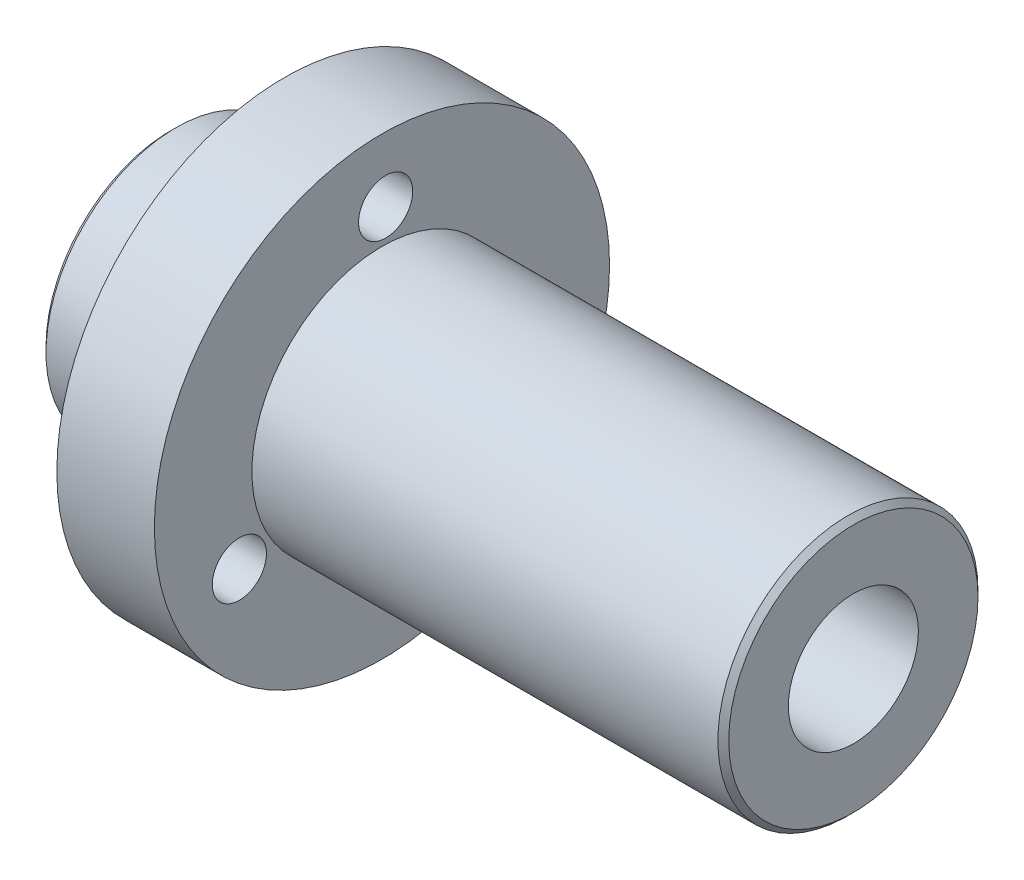
SolidWorks part; units mm, degrees
ref_plane "Plan de face" through (0, 0, 0) normal (0, 0, 1) x (1, 0, 0)
ref_plane "Plan de dessus" through (0, 0, 0) normal (0, 1, 0) x (1, 0, 0)
ref_plane "Plan de droite" through (0, 0, 0) normal (1, 0, 0) x (0, 0, -1)
sketch "Esquisse1" plane through (0, 0, 0) normal (0, 0, 1) x (1, 0, 0)
  line L0 (21, 42) -> (21, 0)
  line L1 (21, 0) -> (39, 0)
  line L2 (39, 0) -> (39, 42)
  line L3 (39, 42) -> (21, 42)
  line L4 (21, 0) -> (39, 0) construction
revolve "Révolution1" add sketch "Esquisse1" angle 360 about L4
sketch "Esquisse2" plane through (21, 0, 0) normal (-1, 0, 0) x (0, 0, 1)
  circle A0 centre (0, 0) radius 24
extrude "Extrusion1" add sketch "Esquisse2" along normal blind 21
sketch "Esquisse3" plane through (39, 0, 0) normal (1, 0, 0) x (0, 0, -1)
  circle A0 centre (0, 0) radius 24
extrude "Extrusion2" add sketch "Esquisse3" along normal blind 87
hole_wizard "Diamètre du perçage M10.0 (10)1" positions "Esquisse5" profile "Esquisse4" hole size "M10.0" standard "Ansi Métrique"
sketch "Esquisse5" plane through (39, 0, 0) normal (1, 0, 0) x (0, 0, -1)
  point P0 (25.6331, -15.5866)
sketch "Esquisse4" plane through (39, -15.5866, -25.6331) normal (0, 1, 0) x (0, 0, -1)
  line L0 (0, 0) -> (0, 18)
  line L1 (0, 18) -> (5, 18)
  line L2 (5, 18) -> (5, 0)
  line L5 (5, 0) -> (0, 0)
  line L11 (0, -6.35) -> (0, 107.95) construction
  dimension "Diamètre du perçage jusqu'au prochain" = 10
  dimension "Profondeur du perçage jusqu'au prochain" = 18
hole_wizard "Diamètre du perçage M10.0 (10)2" positions "Esquisse7" profile "Esquisse6" hole size "M10.0" standard "Ansi Métrique"
sketch "Esquisse7" plane through (39, 0, 0) normal (1, 0, 0) x (0, 0, -1)
  point P0 (0.6818, 29.9923)
sketch "Esquisse6" plane through (39, 29.9923, -0.6818) normal (0, 1, 0) x (0, 0, -1)
  line L0 (0, 0) -> (0, 18)
  line L1 (0, 18) -> (5, 18)
  line L2 (5, 18) -> (5, 0)
  line L5 (5, 0) -> (0, 0)
  line L11 (0, -6.35) -> (0, 107.95) construction
  dimension "Diamètre du perçage jusqu'au prochain" = 10
  dimension "Profondeur du perçage jusqu'au prochain" = 18
hole_wizard "Diamètre du perçage M10.0 (10)3" positions "Esquisse9" profile "Esquisse8" hole size "M10.0" standard "Ansi Métrique"
sketch "Esquisse9" plane through (39, 0, 0) normal (1, 0, 0) x (0, 0, -1)
  point P0 (-26.315, -14.4056)
sketch "Esquisse8" plane through (39, -14.4056, 26.315) normal (0, 1, 0) x (0, 0, -1)
  line L0 (0, 0) -> (0, 18)
  line L1 (0, 18) -> (5, 18)
  line L2 (5, 18) -> (5, 0)
  line L5 (5, 0) -> (0, 0)
  line L11 (0, -6.35) -> (0, 107.95) construction
  dimension "Diamètre du perçage jusqu'au prochain" = 10
  dimension "Profondeur du perçage jusqu'au prochain" = 18
hole_wizard "Perçage1" positions "Esquisse11" profile "Esquisse10" legacy end condition up to next
sketch "Esquisse11" plane through (0, 0, 0) normal (-1, 0, 0) x (0, 0, 1)
  point P0 (0, 0)
sketch "Esquisse10" plane through (0, 0, 0) normal (0, 1, 0) x (0, 0, 1)
  line L0 (0, 0) -> (0, 126)
  line L1 (0, 126) -> (12, 126)
  line L2 (12, 126) -> (12, 99)
  line L3 (12, 99) -> (18, 99)
  line L4 (18, 99) -> (18, 0)
  line L5 (18, 0) -> (0, 0)
  line L6 (0, 110) -> (0, -10) construction
  dimension "Diamètre" = 24
  dimension "Profondeur" = 126
  dimension "Diamètre chambrage" = 36
  dimension "Profondeur chambrage" = 99
chamfer "Chanfrein1" distance 1 angle 45 2 edges at (126, 0, -24) (0, 0, 24)
